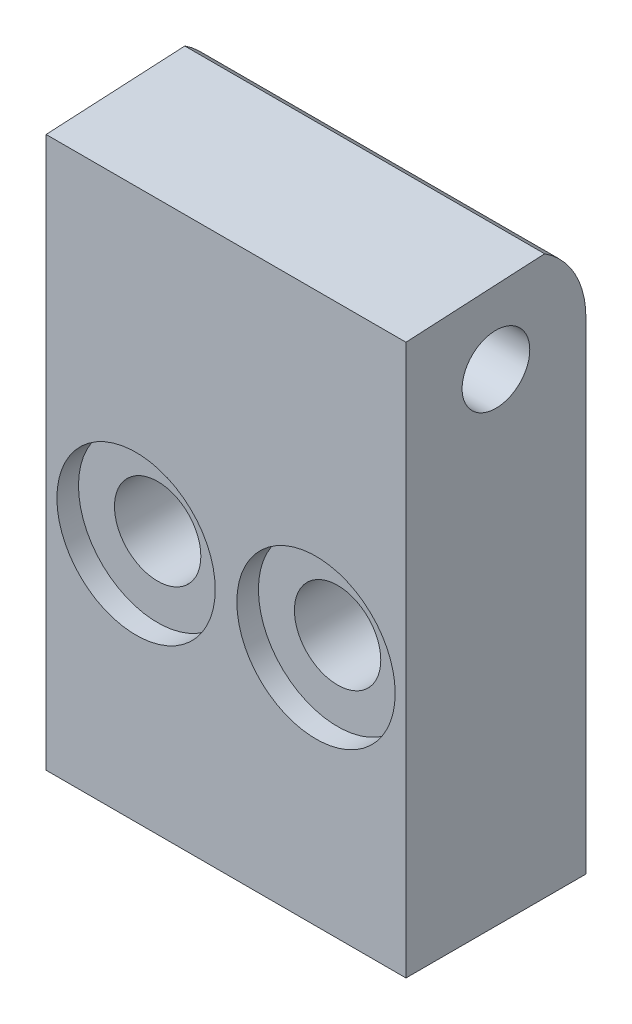
SolidWorks part; units mm, degrees
material "Chrome Stainless Steel"
ref_plane "Front Plane" through (0, 0, 0) normal (0, 0, 1) x (1, 0, 0)
ref_plane "Top Plane" through (0, 0, 0) normal (0, 1, 0) x (1, 0, 0)
ref_plane "Right Plane" through (0, 0, 0) normal (1, 0, 0) x (0, 0, -1)
sketch "Sketch1" plane through (0, 0, 0) normal (0, 0, 1) x (1, 0, 0)
  line L1 (0, 0) -> (12.7, 0)
  line L2 (0, 0) -> (0, 20.193)
  line L3 (0, 20.193) -> (12.7, 20.193)
  line L4 (12.7, 0) -> (12.7, 20.193)
  dimension "D1" = 20.193
  dimension "D2" = 12.7
extrude "Boss-Extrude1" add sketch "Sketch1" along normal blind 6.35
sketch "Sketch2" plane through (0, 0, 6.35) normal (0, 0, 1) x (1, 0, 0)
  line L0 (0, 0) -> (12.7, 0) construction
  line L1 (0, 20.193) -> (0, 0) construction
  line L2 (6.35, 20.193) -> (6.35, 0)
  line L3 (12.7, 20.193) -> (0, 20.193) construction
  circle A0 centre (3.175, 8.509) radius 3.175
  circle A1 centre (9.525, 8.509) radius 3.175
  dimension "D1" = 6.35
  dimension "D2" = 8.509
sketch "Sketch3" plane through (0, 0, 6.35) normal (0, 0, 1) x (1, 0, 0)
  circle A0 centre (3.175, 8.509) radius 1.524
  circle A1 centre (9.525, 8.509) radius 1.524
  dimension "D1" = 3.048
  dimension "D2" = 3.048
extrude "Cut-Extrude1" cut sketch "Sketch3" against normal through all
sketch "Sketch4" plane through (0, 0, 6.35) normal (0, 0, 1) x (1, 0, 0)
  circle A0 centre (3.175, 8.509) radius 2.794
  circle A1 centre (9.525, 8.509) radius 2.794
  dimension "D1" = 5.588
  dimension "D2" = 5.588
extrude "Cut-Extrude2" cut sketch "Sketch4" against normal blind 0.762
sketch "Sketch8" plane through (12.7, 0, 0) normal (1, 0, 0) x (0, 0, -1)
  line L1 (0, 0) -> (0, 20.193) construction
  line L2 (-6.35, 20.193) -> (0, 20.193) construction
  circle A0 centre (-3.175, 17.018) radius 1.1938
  point P7 (-3.175, 17.018)
  dimension "D3" = 2.3876
  dimension "D1" = 3.175
  dimension "D2" = 3.175
extrude "Cut-Extrude5" cut sketch "Sketch8" against normal through all
sketch "Sketch12" plane through (12.7, 0, 0) normal (1, 0, 0) x (0, 0, -1)
  line L0 (-6.35, 20.193) -> (-3.175, 20.193)
  line L1 (0, 17.018) -> (0, 13.9369)
  line L2 (0, 0) -> (0, 20.193) construction
  line L3 (0, 13.9369) -> (3.9241, 13.9369)
  line L4 (3.9241, 13.9369) -> (3.9241, 24.4951)
  line L5 (3.9241, 24.4951) -> (-6.35, 24.4951)
  line L6 (-6.35, 24.4951) -> (-6.35, 20.193)
  arc A0 (-3.175, 20.193) -> (0, 17.018) centre (-3.175, 17.018) cw
  point P12 (0, 20.193)
  dimension "D1" = 3.175
extrude "Cut-Extrude7" cut sketch "Sketch12" against normal through all
sketch "Sketch13" plane through (12.7, 0, 0) normal (1, 0, 0) x (0, 0, -1)
  line L0 (-6.35, 19.431) -> (8.1898, 20.193)
  line L1 (-6.35, 0) -> (-6.35, 20.193) construction
  line L3 (-6.35, 20.193) -> (-3.175, 20.193) construction
  line L4 (-6.35, 19.431) -> (-6.35, 20.193)
  line L5 (-6.35, 20.193) -> (8.1898, 20.193)
  dimension "D1" = 3
  dimension "D2" = 0.762
extrude "Cut-Extrude8" cut sketch "Sketch13" against normal through all
